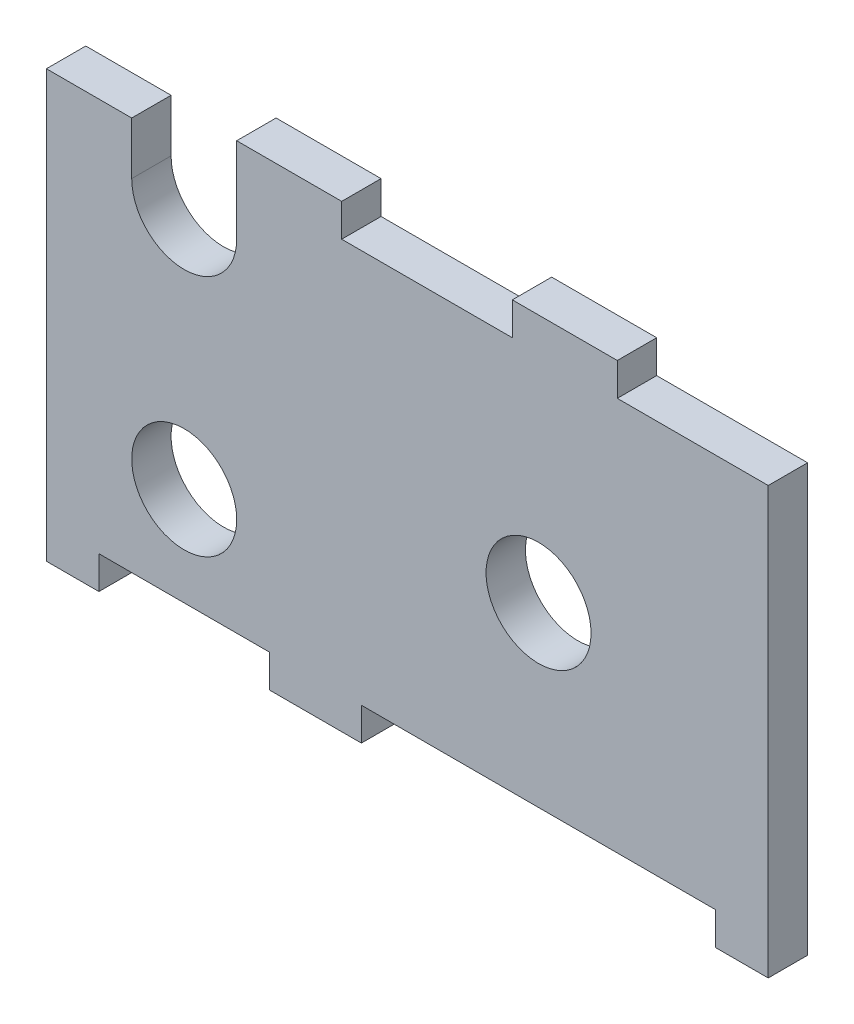
SolidWorks part; units mm, degrees
ref_plane "Plan de face" through (0, 0, 0) normal (0, 0, 1) x (1, 0, 0)
ref_plane "Plan de dessus" through (0, 0, 0) normal (0, 1, 0) x (1, 0, 0)
ref_plane "Plan de droite" through (0, 0, 0) normal (1, 0, 0) x (0, 0, -1)
sketch "Esquisse1" plane through (0, 0, 0) normal (0, 0, 1) x (1, 0, 0)
  line L0 (-21, 15) -> (-27.5, 15)
  line L1 (-13, 17.5) -> (-5, 17.5)
  line L2 (-5, 17.5) -> (-5, 15)
  line L3 (8, 15) -> (-5, 15)
  line L4 (8, 17.5) -> (16, 17.5)
  line L5 (16, 17.5) -> (16, 15)
  line L6 (27.5, 15) -> (16, 15)
  line L7 (27.5, -17.5) -> (27.5, 15)
  line L8 (27.5, -17.5) -> (23.5, -17.5)
  line L9 (23.5, -17.5) -> (23.5, -15)
  line L10 (-3.5, -15) -> (23.5, -15)
  line L11 (-3.5, -17.5) -> (-3.5, -15)
  line L12 (-3.5, -17.5) -> (-10.5, -17.5)
  line L13 (-10.5, -17.5) -> (-10.5, -15)
  line L14 (-23.5, -15) -> (-10.5, -15)
  line L15 (-23.5, -17.5) -> (-23.5, -15)
  line L16 (-23.5, -17.5) -> (-27.5, -17.5)
  line L18 (8, 17.5) -> (8, 15)
  line L20 (-27.5, 15) -> (-27.5, -17.5)
  line L21 (-21, 11) -> (-21, 15)
  line L22 (-13, 17.5) -> (-13, 11)
  circle A0 centre (10, -1.5) radius 4
  arc A1 (-21, 11) -> (-13, 11) centre (-17, 11) ccw
  circle A2 centre (-17, -7.5) radius 4
  dimension "D8" = 8
  dimension "D9" = 8
  dimension "D10" = 4
  dimension "D1" = 55
  dimension "D2" = 4
  dimension "D3" = 13
  dimension "D4" = 7
  dimension "D5" = 27
  dimension "D6" = 35
  dimension "D7" = 2.5
  dimension "D11" = 16
  dimension "D12" = 2.5
  dimension "D13" = 8
  dimension "D14" = 13
  dimension "D15" = 8
  dimension "D16" = 27.5
  dimension "D17" = 10
  dimension "D18" = 1.5
  dimension "D19" = 17
  dimension "D20" = 7.5
  dimension "D21" = 11
extrude "Boss.-Extru.1" add sketch "Esquisse1" along normal blind 3
